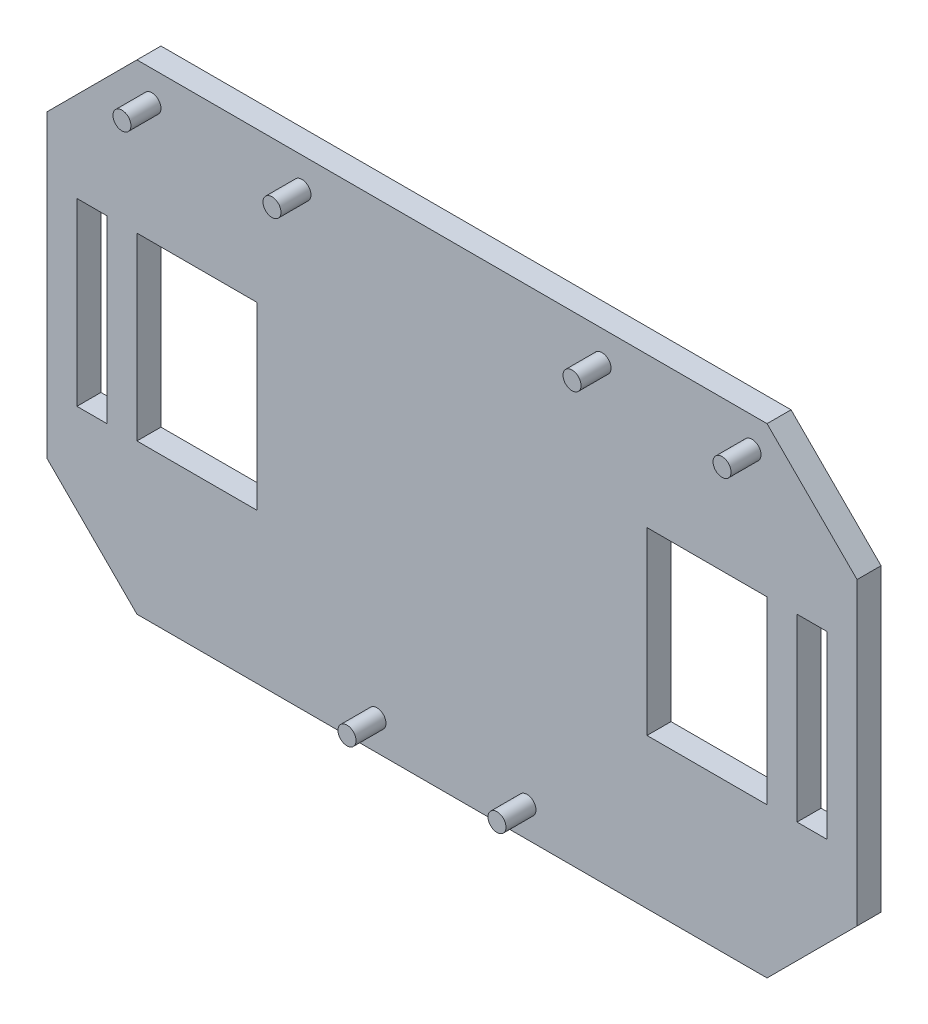
SolidWorks part; units mm, degrees
ref_plane "Front" through (0, 0, 0) normal (0, 0, 1) x (1, 0, 0)
ref_plane "Top" through (0, 0, 0) normal (0, 1, 0) x (1, 0, 0)
ref_plane "Right" through (0, 0, 0) normal (1, 0, 0) x (0, 0, -1)
sketch "Esquisse1" plane through (0, 0, 0) normal (0, 0, 1) x (1, 0, 0)
  line L1 (0, 0) -> (270, 0)
  line L2 (0, 0) -> (0, 160)
  line L3 (0, 160) -> (270, 160)
  line L4 (270, 0) -> (270, 160)
  dimension "D1" = 270
  dimension "D2" = 160
extrude "Boss.-Extru.1" add sketch "Esquisse1" along normal blind 8
chamfer "Chanfrein1" distance 30 angle 45 4 edges at (270, 160, 4) (270, 0, 4) (0, 0, 4) (0, 160, 4)
sketch "Esquisse2" plane through (0, 0, 8) normal (0, 0, 1) x (1, 0, 0)
  line L0 (0, 80) -> (270, 80) construction
  line L1 (0, 130) -> (0, 30) construction
  line L2 (270, 30) -> (270, 130) construction
  line L3 (30, 50) -> (30, 110)
  line L4 (30, 110) -> (70, 110)
  line L5 (70, 110) -> (70, 50)
  line L6 (20, 50) -> (20, 110)
  line L7 (20, 110) -> (10, 110)
  line L8 (10, 110) -> (10, 50)
  line L9 (20, 50) -> (10, 50)
  line L10 (30, 50) -> (70, 50)
  line L11 (135, 80) -> (135, 160) construction
  line L12 (240, 160) -> (30, 160) construction
  line L13 (240, 50) -> (200, 50)
  line L14 (250, 50) -> (260, 50)
  line L15 (260, 110) -> (260, 50)
  line L16 (250, 110) -> (260, 110)
  line L17 (250, 50) -> (250, 110)
  line L18 (200, 110) -> (200, 50)
  line L19 (240, 110) -> (200, 110)
  line L20 (240, 50) -> (240, 110)
  point P15 (10, 80)
  point P16 (20, 80)
  point P17 (70, 80)
  point P18 (30, 80)
  point P30 (240, 80)
  point P31 (200, 80)
  point P32 (250, 80)
  point P33 (260, 80)
  dimension "D1" = 60
  dimension "D2" = 40
  dimension "D3" = 10
  dimension "D4" = 10
  dimension "D5" = 10
extrude "Enlèv. mat.-Extru.1" cut sketch "Esquisse2" against normal blind 8
sketch "Esquisse3" plane through (0, 0, 8) normal (0, 0, 1) x (1, 0, 0)
  line L0 (135, 0) -> (135, 160) construction
  line L1 (30, 0) -> (240, 0) construction
  line L2 (240, 160) -> (30, 160) construction
  line L3 (85, 150) -> (35, 150) construction
  line L4 (185, 150) -> (235, 150) construction
  line L5 (110, 10) -> (135, 10) construction
  circle A0 centre (35, 150) radius 3
  circle A1 centre (85, 150) radius 3
  circle A2 centre (185, 150) radius 3
  circle A3 centre (235, 150) radius 3
  circle A4 centre (110, 10) radius 3
  circle A5 centre (160, 10) radius 3
  dimension "D1" = 6
  dimension "D3" = 50
  dimension "D6" = 6
  dimension "D2" = 50
  dimension "D4" = 10
  dimension "D5" = 10
  dimension "D7" = 50
extrude "Boss.-Extru.2" add sketch "Esquisse3" along normal blind 10
